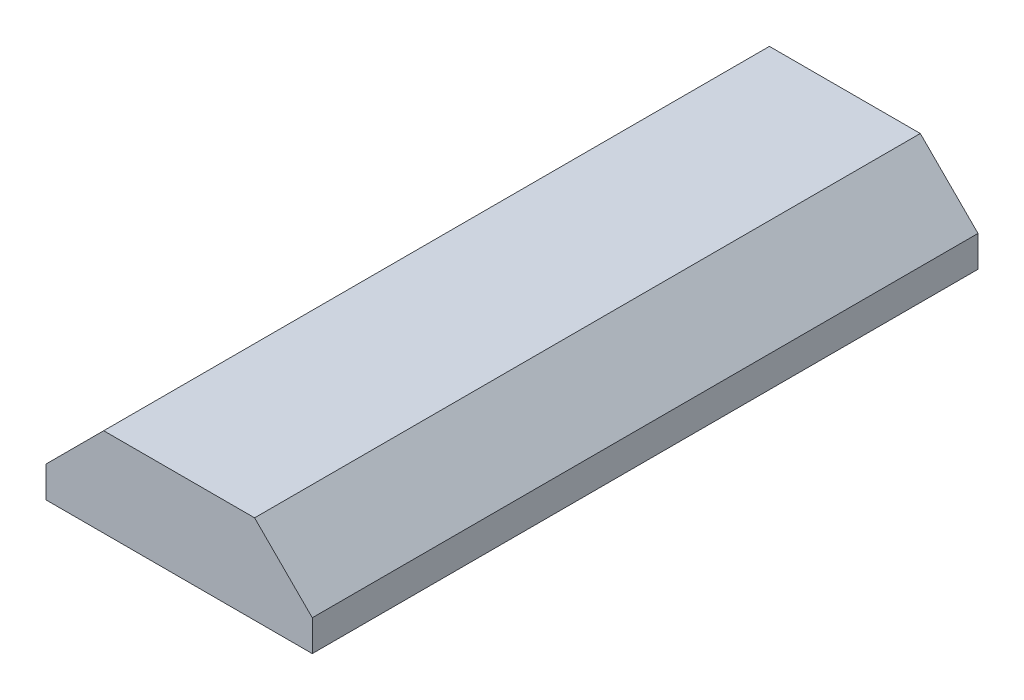
SolidWorks part; units mm, degrees
ref_plane "Ebene vorne" through (0, 0, 0) normal (0, 0, 1) x (1, 0, 0)
ref_plane "Ebene oben" through (0, 0, 0) normal (0, 1, 0) x (1, 0, 0)
ref_plane "Ebene rechts" through (0, 0, 0) normal (1, 0, 0) x (0, 0, -1)
sketch "Skizze1" plane through (0, 0, 0) normal (0, 0, 1) x (1, 0, 0)
  line L0 (0, 0) -> (0, 23680.6173) construction
  line L1 (3.4, 1.8089) -> (-3.4, 1.8089)
  line L2 (-3.4, 1.8089) -> (-6, -0.7911)
  line L3 (-6, -0.7911) -> (-6, -2.1911)
  line L4 (-6, -2.1911) -> (6, -2.1911)
  line L5 (6, -0.7911) -> (6, -2.1911)
  line L6 (3.4, 1.8089) -> (6, -0.7911)
  point P9 (0, -2.1911)
  point P11 (0, 1.8089)
  dimension "D1" = 3.4
  dimension "D2" = 6
  dimension "D3" = 4
  dimension "D4" = 135
extrude "Aufsatz-Linear austragen1" add sketch "Skizze1" along normal blind 30 contours L1 L2 L3 L4 L5 L6
